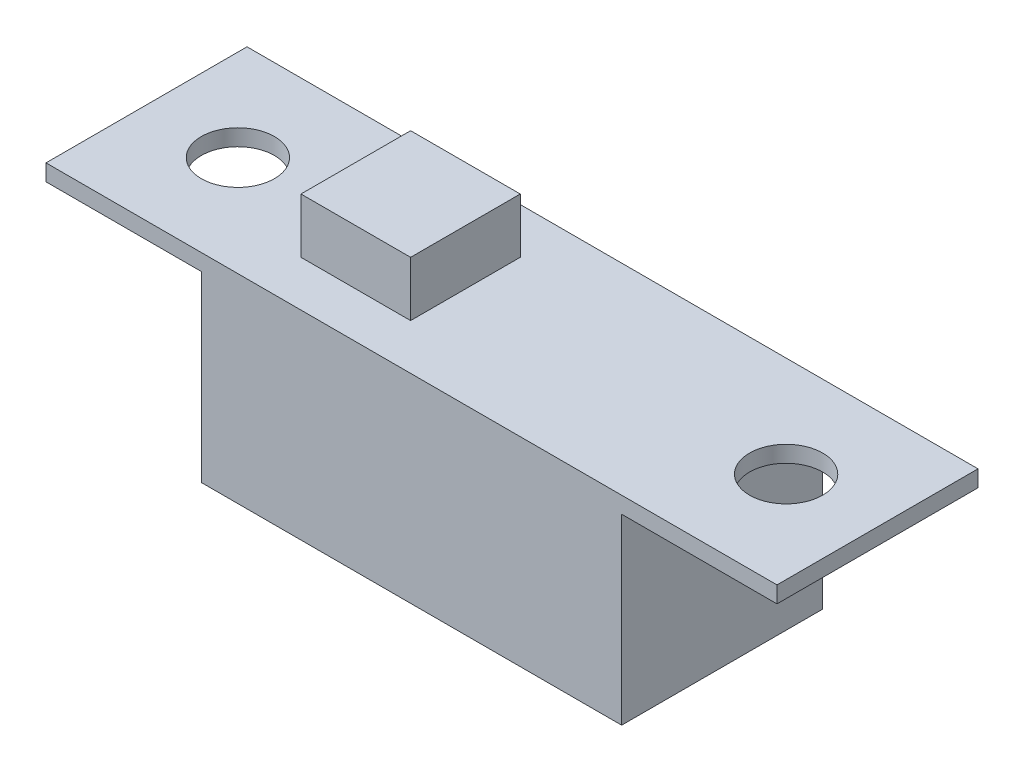
SolidWorks part; units mm, degrees
ref_plane "Alzado" through (0, 0, 0) normal (0, 0, 1) x (1, 0, 0)
ref_plane "Planta" through (0, 0, 0) normal (0, 1, 0) x (1, 0, 0)
ref_plane "Vista lateral" through (0, 0, 0) normal (1, 0, 0) x (0, 0, -1)
sketch "Croquis1" plane through (0, 0, 0) normal (0, 1, 0) x (1, 0, 0)
  line L0 (-10, 0) -> (10, 0) construction
  line L1 (-10, -2.75) -> (10, -2.75)
  line L2 (-10, -2.75) -> (-10, 2.75)
  line L3 (-10, 2.75) -> (10, 2.75)
  line L4 (10, -2.75) -> (10, 2.75)
  line L5 (-10, -2.75) -> (10, 2.75) construction
  line L6 (-10, 2.75) -> (10, -2.75) construction
  line L7 (0, 0) -> (0, -2.75) construction
  circle A0 centre (-7.5, 0) radius 1
  circle A1 centre (7.5, 0) radius 1
  point P0 (0, 0)
  point P12 (0, 0)
  dimension "D3" = 2
  dimension "D1" = 20
  dimension "D2" = 5.5
  dimension "D4" = 15
extrude "Saliente-Extruir1" add sketch "Croquis1" along normal blind 0.45
sketch "Croquis2" plane through (0, 0, 0) normal (0, -1, 0) x (1, 0, 0)
  line L0 (10, -2.75) -> (-10, -2.75) construction
  line L1 (5.75, 2.75) -> (-5.75, 2.75)
  line L2 (5.75, 2.75) -> (5.75, -2.75)
  line L3 (5.75, -2.75) -> (-5.75, -2.75)
  line L4 (-5.75, 2.75) -> (-5.75, -2.75)
  line L5 (5.75, 2.75) -> (-5.75, -2.75) construction
  line L6 (5.75, -2.75) -> (-5.75, 2.75) construction
  point P0 (0, 0)
  dimension "D1" = 11.5
extrude "Saliente-Extruir2" add sketch "Croquis2" along normal blind 5
sketch "Croquis3" plane through (0, 0.45, 0) normal (0, 1, 0) x (1, 0, 0)
  line L1 (-4.2742, 1.5) -> (-1.2742, 1.5)
  line L2 (-4.2742, 1.5) -> (-4.2742, -1.5)
  line L3 (-4.2742, -1.5) -> (-1.2742, -1.5)
  line L4 (-1.2742, 1.5) -> (-1.2742, -1.5)
  line L5 (-4.2742, 1.5) -> (-1.2742, -1.5) construction
  line L6 (-4.2742, -1.5) -> (-1.2742, 1.5) construction
  point P0 (-2.7742, 0)
  point P5 (-2.7742, 0)
  dimension "D1" = 3
  dimension "D2" = 3
extrude "Saliente-Extruir3" add sketch "Croquis3" along normal blind 1.5
